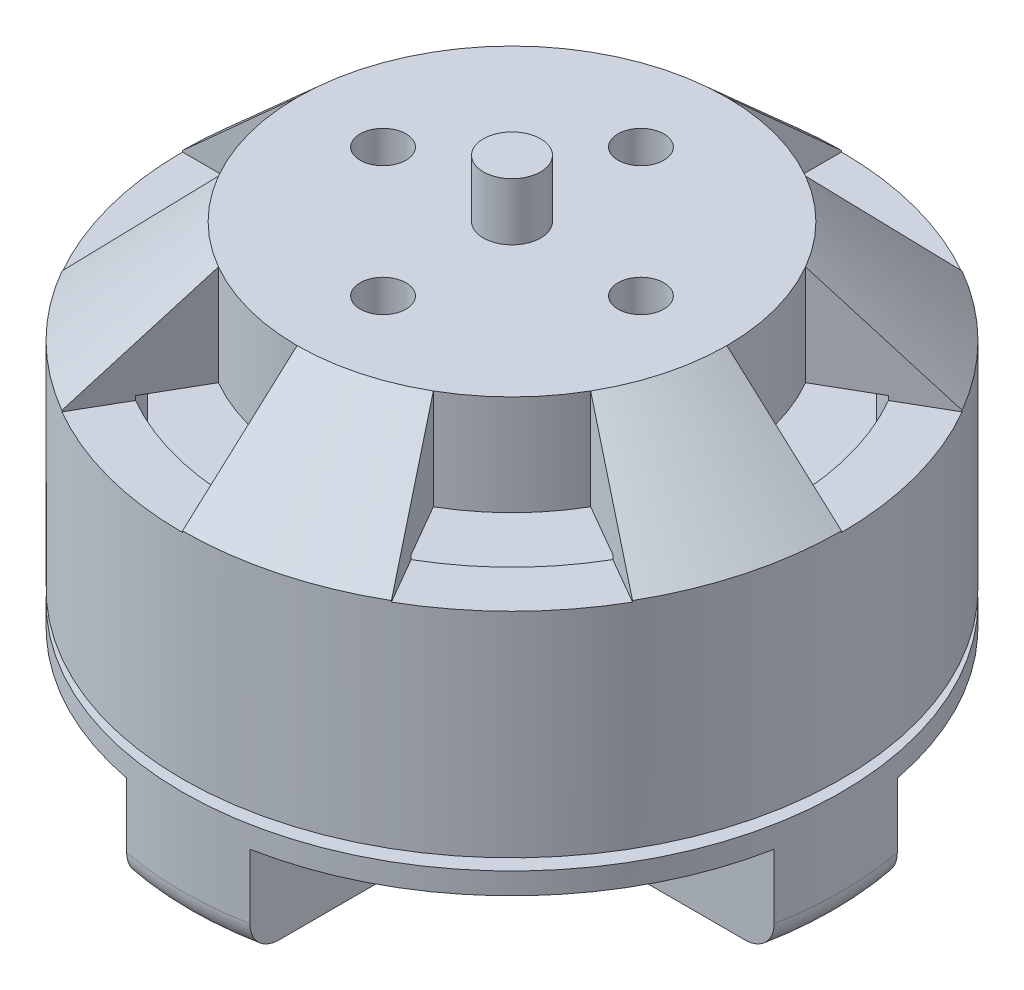
SolidWorks part; units mm, degrees
ref_plane "Front Plane" through (0, 0, 0) normal (0, 0, 1) x (1, 0, 0)
ref_plane "Top Plane" through (0, 0, 0) normal (0, 1, 0) x (1, 0, 0)
ref_plane "Right Plane" through (0, 0, 0) normal (1, 0, 0) x (0, 0, -1)
sketch "Sketch1" plane through (0, 0, 0) normal (0, 1, 0) x (1, 0, 0)
  circle A0 centre (0, 0) radius 11.5
  dimension "D1" = 23
extrude "Boss-Extrude1" add sketch "Sketch1" along normal blind 4
sketch "Sketch2" plane through (0, 4, 0) normal (0, 1, 0) x (1, 0, 0)
  line L0 (0, -9.3175) -> (4.6587, -8.0692)
  line L1 (0, 9.3175) -> (-4.6587, 8.0692)
  line L2 (-4.6587, 8.0692) -> (-8.0692, 4.6587)
  line L3 (-8.0692, 4.6587) -> (-9.3175, 0)
  line L4 (-9.3175, 0) -> (-8.0692, -4.6587)
  line L5 (-8.0692, -4.6587) -> (-4.6587, -8.0692)
  line L6 (-4.6587, -8.0692) -> (0, -9.3175)
  line L7 (4.6587, -8.0692) -> (8.0692, -4.6587)
  line L8 (8.0692, -4.6587) -> (9.3175, 0)
  line L9 (9.3175, 0) -> (8.0692, 4.6587)
  line L10 (8.0692, 4.6587) -> (4.6587, 8.0692)
  line L11 (4.6587, 8.0692) -> (0, 9.3175)
  circle A0 centre (0, 0) radius 9 construction
  dimension "D1" = 18
extrude "Boss-Extrude2" add sketch "Sketch2" along normal blind 6 separate body
sketch "Sketch3" plane through (0, 0, 0) normal (0, -1, 0) x (1, 0, 0)
  line L0 (-2.15, 11.2972) -> (-2.15, 4.65)
  line L1 (2.15, 11.2972) -> (2.15, 4.65)
  line L2 (-11.2972, 2.15) -> (-4.65, 2.15)
  line L3 (11.2972, -2.15) -> (4.65, -2.15)
  line L4 (-2.15, -4.65) -> (-2.15, -11.2972)
  line L5 (-4.65, -2.15) -> (-11.2972, -2.15)
  line L6 (2.15, -4.65) -> (2.15, -11.2972)
  line L7 (4.65, 2.15) -> (11.2972, 2.15)
  circle A0 centre (0, 0) radius 6 construction
  circle A1 centre (0, 0) radius 8 construction
  circle A2 centre (0, 8) radius 1
  circle A3 centre (6, 0) radius 1
  circle A4 centre (0, -8) radius 1
  circle A5 centre (-6, 0) radius 1
  circle A6 centre (0, 0) radius 11.5 construction
  arc A7 (-11.2972, -2.15) -> (-2.15, -11.2972) centre (0, 0) ccw
  arc A8 (2.15, -11.2972) -> (11.2972, -2.15) centre (0, 0) ccw
  arc A9 (-2.15, 11.2972) -> (-11.2972, 2.15) centre (0, 0) ccw
  arc A10 (11.2972, 2.15) -> (2.15, 11.2972) centre (0, 0) ccw
  arc A11 (-2.15, -4.65) -> (-4.65, -2.15) centre (-4.65, -4.65) ccw
  arc A12 (4.65, -2.15) -> (2.15, -4.65) centre (4.65, -4.65) ccw
  arc A13 (2.15, 4.65) -> (4.65, 2.15) centre (4.65, 4.65) ccw
  arc A14 (-2.15, 4.65) -> (-4.65, 2.15) centre (-4.65, 4.65) cw
  point P18 (-2.15, -2.15)
  point P29 (2.15, -2.15)
  point P32 (2.15, 2.15)
  dimension "D1" = 16
  dimension "D2" = 12
  dimension "D3" = 2.15
  dimension "D7" = 2.5
  dimension "D4" = 4.3
  dimension "D5" = 2.15
  dimension "D6" = 4.3
extrude "Cut-Extrude1" cut sketch "Sketch3" against normal offset from surface (3.25 mm away) 0.75 up to face at (0, 4, 11.5)
ref_plane "Plane1" through (0, 0, 0) normal (1, 0, 0) x (0, 0, -1)
sketch "Sketch4" plane through (0, 0, 0) normal (1, 0, 0) x (0, 0, -1)
  line L0 (-11.5, 4.3976) -> (-11.5, 11.8976)
  line L1 (-11.5, 11.8976) -> (-7.5, 15.5)
  line L2 (-7.5, 15.5) -> (-1, 15.5)
  line L3 (0, 15.5) -> (0, 11)
  line L4 (-1, 12) -> (-9.6175, 12)
  line L5 (-9.6175, 12) -> (-9.6175, 4.3976)
  line L6 (-9.6175, 4.3976) -> (-11.5, 4.3976)
  line L7 (-9.3175, 10) -> (-9.3175, 4) construction
  line L8 (-4.6587, 10) -> (0, 10) construction
  line L9 (-11.2972, 0) -> (-4.65, 0) construction
  line L10 (0, 19.1167) -> (0, -2.5525) construction
  line L11 (-1, 15.5) -> (-1, 17.5)
  line L12 (0, 11) -> (0, 10)
  line L13 (0, 10) -> (-1, 10)
  line L14 (-1, 12) -> (-1, 10)
  line L15 (-1, 17.5) -> (0, 17.5)
  line L16 (0, 17.5) -> (0, 15.5)
  dimension "D1" = 7.5
  dimension "D2" = 0.3
  dimension "D3" = 11.5
  dimension "D4" = 2
  dimension "D5" = 15.5
  dimension "D6" = 1
  dimension "D7" = 2
revolve "Revolve2" add sketch "Sketch4" angle 360 about L10
sketch "Sketch6" plane through (0, 15.5, 0) normal (0, 1, 0) x (1, 0, 0)
  line L0 (-7.5, 0) -> (7.5, 0) construction
  line L1 (0, 7.5) -> (0, 11.5)
  line L13 (6.4952, 3.75) -> (-6.4952, -3.75) construction
  line L14 (-6.4952, 3.75) -> (6.4952, -3.75) construction
  line L15 (3.75, -6.4952) -> (-3.75, 6.4952) construction
  line L16 (3.75, 6.4952) -> (-3.75, -6.4952) construction
  line L17 (0, -7.5) -> (0, 7.5) construction
  line L18 (-3.75, 6.4952) -> (-5.75, 9.9593)
  line L19 (-6.4952, 3.75) -> (-9.9593, 5.75)
  line L20 (-11.5, 0) -> (-7.5, 0)
  line L21 (-6.4952, -3.75) -> (-9.9593, -5.75)
  line L22 (-3.75, -6.4952) -> (-5.75, -9.9593)
  line L23 (3.75, -6.4952) -> (5.75, -9.9593)
  line L24 (0, -7.5) -> (0, -11.5)
  line L27 (6.4952, -3.75) -> (9.9593, -5.75)
  line L28 (7.5, 0) -> (11.5, 0)
  line L29 (6.4952, 3.75) -> (9.9593, 5.75)
  line L30 (3.75, 6.4952) -> (5.75, 9.9593)
  arc A0 (-3.75, 6.4952) -> (-6.4952, 3.75) centre (0, 0) ccw
  arc A1 (-5.75, 9.9593) -> (-9.9593, 5.75) centre (0, 0) ccw
  arc A2 (-7.5, 0) -> (-6.4952, -3.75) centre (0, 0) ccw
  arc A3 (-3.75, -6.4952) -> (0, -7.5) centre (0, 0) ccw
  arc A4 (-11.5, 0) -> (-9.9593, -5.75) centre (0, 0) ccw
  arc A5 (-5.75, -9.9593) -> (0, -11.5) centre (0, 0) ccw
  arc A6 (3.75, -6.4952) -> (6.4952, -3.75) centre (0, 0) ccw
  arc A7 (5.75, -9.9593) -> (9.9593, -5.75) centre (0, 0) ccw
  arc A8 (7.5, 0) -> (6.4952, 3.75) centre (0, 0) ccw
  arc A9 (11.5, 0) -> (9.9593, 5.75) centre (0, 0) ccw
  arc A10 (3.75, 6.4952) -> (0, 7.5) centre (0, 0) ccw
  arc A11 (5.75, 9.9593) -> (0, 11.5) centre (0, 0) ccw
extrude "Cut-Extrude2" cut sketch "Sketch6" against normal offset from surface (3.65 mm away) 8.6 up to face at (-5.2844, 3.25, 5.2844)
sketch "Sketch9" plane through (0, 3.25, 0) normal (0, -1, 0) x (1, 0, 0)
  line L0 (-4.65, -2.15) -> (-11.2972, -2.15) construction
  line L1 (-2.15, -11.2972) -> (-2.15, -4.65) construction
  line L2 (2.15, -4.65) -> (2.15, -11.2972) construction
  line L3 (11.2972, -2.15) -> (4.65, -2.15) construction
  line L4 (4.65, 2.15) -> (11.2972, 2.15) construction
  line L5 (2.15, 11.2972) -> (2.15, 4.65) construction
  line L6 (-2.15, 4.65) -> (-2.15, 11.2972) construction
  line L7 (-11.2972, 2.15) -> (-4.65, 2.15) construction
  line L8 (-4.65, -2.15) -> (-9.2535, -2.15)
  line L9 (-2.15, -9.2535) -> (-2.15, -4.65)
  line L10 (2.15, -4.65) -> (2.15, -9.2535)
  line L11 (9.2535, -2.15) -> (4.65, -2.15)
  line L12 (4.65, 2.15) -> (9.2535, 2.15)
  line L13 (2.15, 9.2535) -> (2.15, 4.65)
  line L14 (-2.15, 4.65) -> (-2.15, 9.2535)
  line L15 (-9.2535, 2.15) -> (-4.65, 2.15)
  arc A0 (-2.15, -4.65) -> (-4.65, -2.15) centre (-4.65, -4.65) ccw construction
  arc A1 (4.65, -2.15) -> (2.15, -4.65) centre (4.65, -4.65) ccw construction
  arc A2 (2.15, 4.65) -> (4.65, 2.15) centre (4.65, 4.65) ccw construction
  arc A3 (-4.65, 2.15) -> (-2.15, 4.65) centre (-4.65, 4.65) ccw construction
  arc A4 (-2.15, -4.65) -> (-4.65, -2.15) centre (-4.65, -4.65) ccw
  arc A5 (4.65, -2.15) -> (2.15, -4.65) centre (4.65, -4.65) ccw
  arc A6 (2.15, 4.65) -> (4.65, 2.15) centre (4.65, 4.65) ccw
  arc A7 (-4.65, 2.15) -> (-2.15, 4.65) centre (-4.65, 4.65) ccw
  arc A8 (-9.2535, -2.15) -> (-2.15, -9.2535) centre (0, 0) ccw
  arc A9 (-2.15, 9.2535) -> (-9.2535, 2.15) centre (0, 0) ccw
  arc A10 (9.2535, 2.15) -> (2.15, 9.2535) centre (0, 0) ccw
  arc A11 (2.15, -9.2535) -> (9.2535, -2.15) centre (0, 0) ccw
  dimension "D1" = 19
extrude "Cut-Extrude3" cut sketch "Sketch9" against normal blind 0.75
fillet "Fillet1" radius 1 4 edges at (-11.5, 0, 0) (11.5, 0, 0) (0, 0, 11.5) (0, 0, -11.5)
hole_wizard "M2 Tapped Hole1" positions "Sketch12" profile "Sketch10" tap size "M2" standard "DIN"
sketch "Sketch12" plane through (0, 15.5, 0) normal (0, 1, 0) x (1, 0, 0)
  line L0 (0, -3.3) -> (0, 3.3) construction
  point P0 (-4.5, 0)
  point P2 (0, 4.5)
  point P6 (4.5, 0)
  point P8 (0, -4.5)
  dimension "D1" = 9
  dimension "D2" = 9
  dimension "D3" = 4.5
  dimension "D4" = 4.5
sketch "Sketch10" plane through (-4.5, 15.5, 0) normal (1, 0, 0) x (0, 0, 1)
  line L0 (0, 0) -> (0, 3.7807)
  line L1 (0, 3.7807) -> (0.8, 3.3)
  line L2 (0.8, 3.3) -> (0.8, 0)
  line L5 (0.8, 0) -> (0, 0)
  line L10 (0, 3.7807) -> (-0.8, 3.3) construction
  line L11 (0, -6.35) -> (0, 107.95) construction
  dimension "Tap Drill Dia." = 1.6
  dimension "Tap Drill Depth" = 3.3
  dimension "Drill Angle" = 118
cosmetic thread "Hole Thread1" parameters "D1"=3.3, "D2"=2
cosmetic thread "Hole Thread2" parameters "D1"=3.3, "D2"=2
cosmetic thread "Hole Thread3" parameters "D1"=3.3, "D2"=2
cosmetic thread "Hole Thread4" parameters "D1"=3.3, "D2"=2
